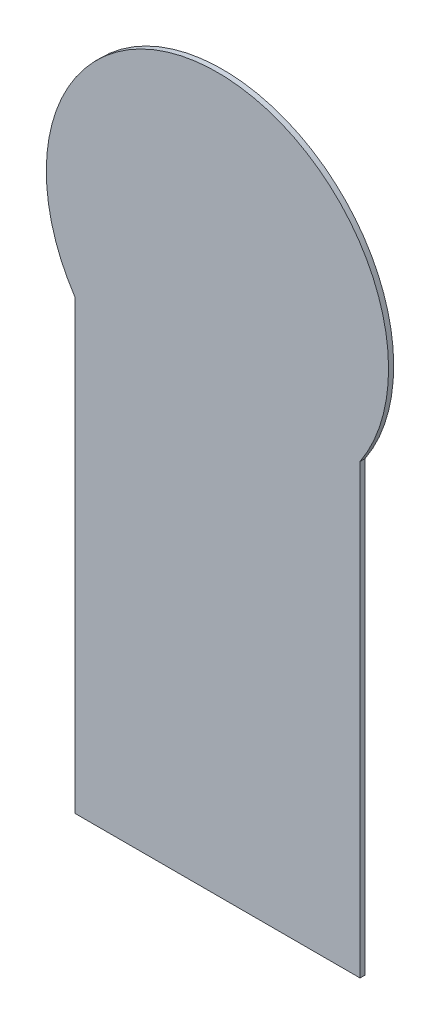
SolidWorks part; units mm, degrees
ref_plane "Front Plane" through (0, 0, 0) normal (0, 0, 1) x (1, 0, 0)
ref_plane "Top Plane" through (0, 0, 0) normal (0, 1, 0) x (1, 0, 0)
ref_plane "Right Plane" through (0, 0, 0) normal (1, 0, 0) x (0, 0, -1)
sketch "Sketch1" plane through (0, 0, 0) normal (0, 0, 1) x (1, 0, 0)
  line L2 (-3.175, -2.1061) -> (-3.175, -12.065)
  line L3 (-3.175, -12.065) -> (3.175, -12.065)
  line L4 (3.175, -2.1061) -> (3.175, -12.065)
  arc A0 (3.175, -2.1061) -> (-3.175, -2.1061) centre (0, 0) ccw
  dimension "D1" = 7.62
  dimension "D4" = 12.065
  dimension "D2" = 6.35
  dimension "D3" = 3.175
extrude "Boss-Extrude1" add sketch "Sketch1" along normal blind 0.1143
sketch "Sketch2" plane through (0, 0, 0) normal (0, 0, -1) x (-1, 0, 0)
  line L0 (-2.0344, -12.065) -> (-2.0344, -3.0137)
  line L1 (3.175, -12.065) -> (-3.175, -12.065) construction
  line L2 (-0.5104, -12.065) -> (-0.5104, -6.8345)
  line L3 (-0.5433, -6.6329) -> (-1.2277, -4.589)
  line L4 (-1.2606, -4.3873) -> (-1.2606, -3.1479)
  line L5 (0, 3.81) -> (0, -12.065) construction
  line L6 (-0.5104, -12.065) -> (-2.0344, -12.065)
  line L7 (0.5104, -12.065) -> (2.0344, -12.065)
  line L8 (2.0344, -12.065) -> (2.0344, -3.0137)
  line L9 (1.2606, -4.3873) -> (1.2606, -3.1479)
  line L10 (0.5433, -6.6329) -> (1.2277, -4.589)
  line L11 (0.5104, -12.065) -> (0.5104, -6.8345)
  line L12 (-1.2606, -3.1479) -> (-1.2606, -2.7037)
  line L13 (1.2606, -3.1479) -> (1.2606, -2.7037)
  line L14 (-2.5877, 0.127) -> (2.664, 0.127)
  line L15 (-2.5546, 0.4318) -> (2.6318, 0.4318)
  line L16 (-2.667, 0) -> (2.667, 0) construction
  line L17 (-1.6335, 2.1082) -> (-1.9259, 2.6146)
  line L18 (2.5877, -0.127) -> (-2.664, -0.127)
  line L19 (2.5546, -0.4318) -> (-2.6318, -0.4318)
  line L20 (2.5773, -0.6858) -> (-2.4984, -0.6858)
  line L21 (2.4762, -0.9906) -> (-2.3939, -0.9906)
  line L22 (-2.3588, -1.2446) -> (2.2723, -1.2446)
  line L23 (-2.1708, -1.5494) -> (2.0764, -1.5494)
  line L24 (1.9649, -1.8034) -> (-1.8601, -1.8034)
  line L25 (1.6335, -2.1082) -> (-1.5059, -2.1082)
  line L26 (2.4984, 0.6858) -> (-2.5773, 0.6858)
  line L27 (2.3939, 0.9906) -> (-2.4762, 0.9906)
  line L28 (-2.2723, 1.2446) -> (2.3588, 1.2446)
  line L29 (-2.0764, 1.5494) -> (2.1708, 1.5494)
  line L30 (1.8601, 1.8034) -> (-1.9649, 1.8034)
  line L31 (1.5059, 2.1082) -> (-1.6335, 2.1082)
  line L32 (1.6878, 2.2023) -> (1.9259, 2.6146)
  arc A0 (2.0764, -1.5494) -> (2.2723, -1.2446) centre (0, 0) ccw
  arc A1 (1.5311, -2.1838) -> (1.6335, -2.1082) centre (0, 0) ccw
  arc A2 (3.175, -2.1061) -> (-3.175, -2.1061) centre (0, 0) ccw construction
  arc A3 (2.2484, -2.5383) -> (2.1151, 2.6504) centre (0, 0) ccw
  arc A4 (-1.8601, -1.8034) -> (-1.5059, -2.1082) centre (0, 0) ccw
  arc A5 (1.9649, -1.8034) -> (2.4762, -0.9906) centre (0, 0) ccw
  arc A6 (2.5546, -0.4318) -> (2.5877, -0.127) centre (0, 0) ccw
  arc A7 (-2.1708, -1.5494) -> (-1.5311, -2.1838) centre (0, 0) ccw
  arc A8 (-2.4984, -0.6858) -> (-2.3939, -0.9906) centre (0, 0) ccw
  arc A9 (2.5773, -0.6858) -> (2.664, 0.127) centre (0, 0) ccw
  arc A10 (-2.6318, -0.4318) -> (-2.3588, -1.2446) centre (0, 0) ccw
  arc A11 (2.4984, 0.6858) -> (2.3939, 0.9906) centre (0, 0) ccw
  arc A12 (-2.5546, 0.4318) -> (-2.5877, 0.127) centre (0, 0) ccw
  arc A13 (1.8601, 1.8034) -> (1.5059, 2.1082) centre (0, 0) ccw
  arc A14 (-2.0764, 1.5494) -> (-2.2723, 1.2446) centre (0, 0) ccw
  arc A15 (-2.1151, 2.6504) -> (-2.2484, -2.5383) centre (0, 0) ccw
  arc A16 (-1.9649, 1.8034) -> (-2.4762, 0.9906) centre (0, 0) ccw
  arc A17 (-1.5311, -2.1838) -> (-1.2606, -2.7037) centre (-1.8956, -2.7037) cw
  arc A18 (1.5311, -2.1838) -> (1.2606, -2.7037) centre (1.8956, -2.7037) ccw
  arc A19 (-2.2484, -2.5383) -> (-2.0344, -3.0137) centre (-2.6694, -3.0137) cw
  arc A20 (2.2484, -2.5383) -> (2.0344, -3.0137) centre (2.6694, -3.0137) ccw
  arc A21 (-1.2606, -4.3873) -> (-1.2277, -4.589) centre (-0.6256, -4.3873) ccw
  arc A22 (1.2606, -4.3873) -> (1.2277, -4.589) centre (0.6256, -4.3873) cw
  arc A23 (-0.5433, -6.6329) -> (-0.5104, -6.8345) centre (-1.1454, -6.8345) cw
  arc A24 (0.5433, -6.6329) -> (0.5104, -6.8345) centre (1.1454, -6.8345) ccw
  arc A25 (-2.1151, 2.6504) -> (-1.9259, 2.6146) centre (-2.0359, 2.5511) cw
  arc A26 (1.9259, 2.6146) -> (2.1151, 2.6504) centre (2.0359, 2.5511) cw
  arc A27 (-2.5773, 0.6858) -> (-2.664, -0.127) centre (0, 0) ccw
  arc A28 (2.6318, 0.4318) -> (2.3588, 1.2446) centre (0, 0) ccw
  arc A29 (2.1708, 1.5494) -> (1.7161, 2.0415) centre (0, 0) ccw
  arc A30 (1.6878, 2.2023) -> (1.7161, 2.0415) centre (1.7978, 2.1388) ccw
  point P67 (-2.0344, -2.7128)
  point P70 (2.0344, -2.7128)
  point P73 (-1.2606, -4.4908)
  point P76 (1.2606, -4.4908)
  point P79 (-0.5104, -6.731)
  point P82 (0.5104, -6.731)
  point P85 (-1.9981, 2.7397)
  point P88 (1.9981, 2.7397)
  point P90 (1.6335, 2.1082)
  dimension "D1" = 5.1816
  dimension "D2" = 5.334
  dimension "D24" = 0.635
  dimension "D25" = 0.635
  dimension "D26" = 0.635
  dimension "D27" = 0.635
  dimension "D28" = 0.635
  dimension "D29" = 0.635
  dimension "D30" = 0.635
  dimension "D31" = 0.635
  dimension "D32" = 0.127
  dimension "D33" = 0.127
  dimension "D34" = 0.127
  dimension "D3" = 5.334
  dimension "D4" = 1.524
  dimension "D5" = 0.5104
  dimension "D6" = 1.778
  dimension "D7" = 0.3048
  dimension "D8" = 0.3048
  dimension "D9" = 0.127
  dimension "D10" = 0.254
  dimension "D11" = 0.254
  dimension "D12" = 0.3048
  dimension "D13" = 0.254
  dimension "D14" = 0.3048
  dimension "D15" = 0.254
  dimension "D16" = 0.3048
  dimension "D17" = 0.254
  dimension "D18" = 0.3048
  dimension "D19" = 0.254
  dimension "D20" = 0.3048
  dimension "D21" = 0.254
  dimension "D22" = 0.3048
  dimension "D23" = 30
extrude "Boss-Extrude3" add sketch "Sketch2" against normal blind 0.0508 separate body
